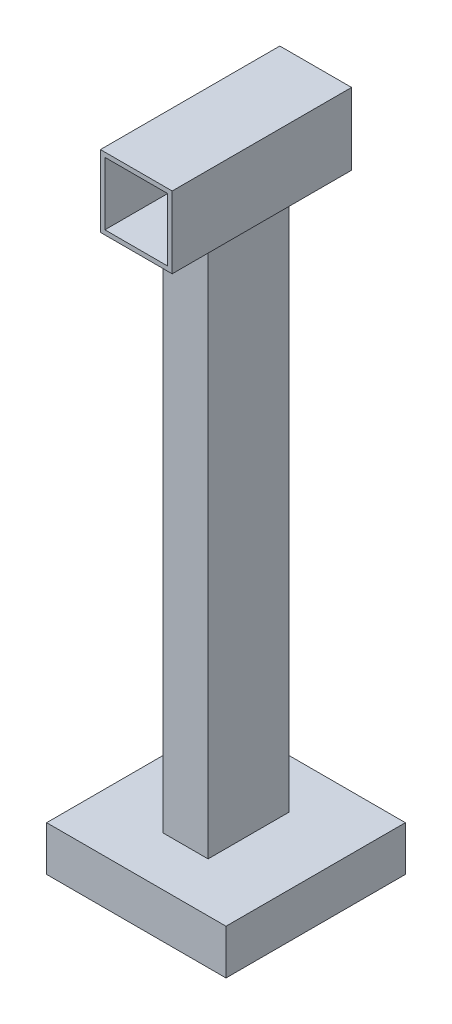
SolidWorks part; units mm, degrees
ref_plane "Plan de face" through (0, 0, 0) normal (0, 0, 1) x (1, 0, 0)
ref_plane "Plan de dessus" through (0, 0, 0) normal (0, 1, 0) x (1, 0, 0)
ref_plane "Plan de droite" through (0, 0, 0) normal (1, 0, 0) x (0, 0, -1)
sketch "Esquisse2" plane through (0, 0, 0) normal (0, 0, 1) x (1, 0, 0)
  line L1 (-20, 20) -> (20, 20)
  line L2 (-20, 20) -> (-20, -20)
  line L3 (-20, -20) -> (20, -20)
  line L4 (20, 20) -> (20, -20)
  line L5 (-20, 20) -> (20, -20) construction
  line L6 (-20, -20) -> (20, 20) construction
  line L8 (-17.5, 17.5) -> (17.5, 17.5)
  line L9 (-17.5, 17.5) -> (-17.5, -17.5)
  line L10 (-17.5, -17.5) -> (17.5, -17.5)
  line L11 (17.5, 17.5) -> (17.5, -17.5)
  line L12 (-17.5, 17.5) -> (17.5, -17.5) construction
  line L13 (-17.5, -17.5) -> (17.5, 17.5) construction
  point P0 (0, 0)
  point P6 (0, 0)
  dimension "D1" = 40
  dimension "D2" = 40
  dimension "D3" = 35
extrude "Boss.-Extru.1" add sketch "Esquisse2" along normal blind 100
sketch "Esquisse3" plane through (0, -20, 0) normal (0, -1, 0) x (1, 0, 0)
  line L0 (0, -12.4145) -> (0, 233.1361) construction
  line L1 (-20, 50) -> (20, 50) construction
  line L2 (-20, 100) -> (-20, 0) construction
  line L3 (20, 100) -> (20, 0) construction
  line L5 (-12.5, 72.5) -> (12.5, 72.5)
  line L6 (-12.5, 72.5) -> (-12.5, 27.5)
  line L7 (-12.5, 27.5) -> (12.5, 27.5)
  line L8 (12.5, 72.5) -> (12.5, 27.5)
  line L9 (-12.5, 72.5) -> (12.5, 27.5) construction
  line L10 (-12.5, 27.5) -> (12.5, 72.5) construction
  point P9 (0, 50)
  dimension "D1" = 25
  dimension "D2" = 45
extrude "Boss.-Extru.2" add sketch "Esquisse3" along normal blind 300
sketch "Esquisse4" plane through (0, -320, 0) normal (0, -1, 0) x (1, 0, 0)
  line L0 (0, 72.5) -> (0, 27.5) construction
  line L1 (12.5, 72.5) -> (-12.5, 72.5) construction
  line L2 (-12.5, 27.5) -> (12.5, 27.5) construction
  line L3 (-12.5, 50) -> (12.5, 50) construction
  line L4 (-12.5, 72.5) -> (-12.5, 27.5) construction
  line L5 (12.5, 27.5) -> (12.5, 72.5) construction
  line L7 (-50, 100) -> (50, 100)
  line L8 (-50, 100) -> (-50, 0)
  line L9 (-50, 0) -> (50, 0)
  line L10 (50, 100) -> (50, 0)
  line L11 (-50, 100) -> (50, 0) construction
  line L12 (-50, 0) -> (50, 100) construction
  point P12 (0, 50)
  dimension "D1" = 100
  dimension "D2" = 100
extrude "Boss.-Extru.3" add sketch "Esquisse4" along normal blind 25
